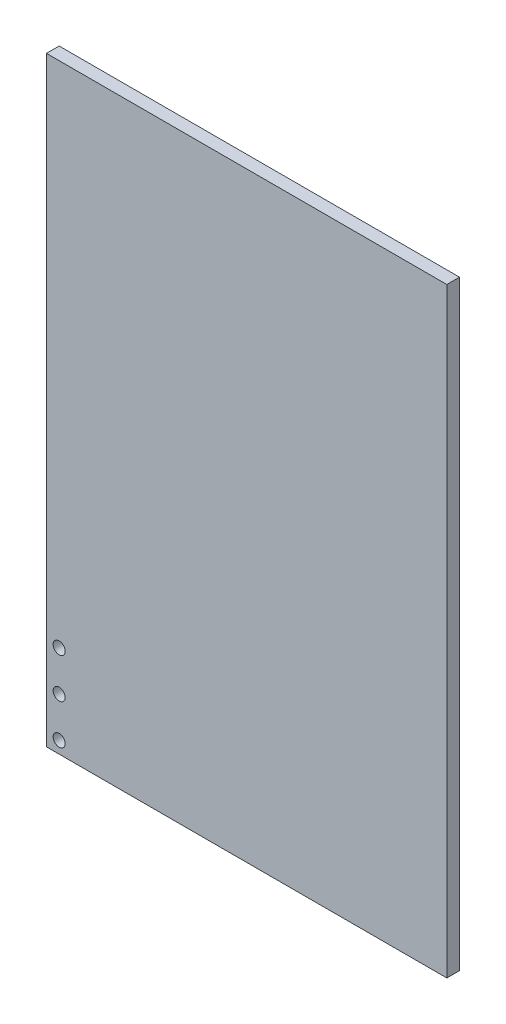
SolidWorks part; units mm, degrees
ref_plane "Front Plane" through (0, 0, 0) normal (0, 0, 1) x (1, 0, 0)
ref_plane "Top Plane" through (0, 0, 0) normal (0, 1, 0) x (1, 0, 0)
ref_plane "Right Plane" through (0, 0, 0) normal (1, 0, 0) x (0, 0, -1)
sketch "Sketch1" plane through (0, 0, 0) normal (0, 1, 0) x (1, 0, 0)
  line L1 (0, 0) -> (100, 0)
  line L2 (0, 0) -> (0, 3.175)
  line L3 (0, 3.175) -> (100, 3.175)
  line L4 (100, 0) -> (100, 3.175)
  dimension "D1" = 100
  dimension "D2" = 3.175
extrude "Boss-Extrude1" add sketch "Sketch1" along normal blind 150
sketch "Sketch2" plane through (0, 0, 0) normal (0, 0, 1) x (1, 0, 0)
  line L5 (0, 0) -> (6.35, 0)
  line L6 (0, 0) -> (0, 16)
  line L7 (0, 16) -> (6.35, 16)
  line L8 (6.35, 0) -> (6.35, 16)
  circle A3 centre (3.175, 13) radius 1.5
  circle A4 centre (3.175, 3) radius 1.5
  dimension "D5" = 3
  dimension "D6" = 3
  dimension "D7" = 3.175
  dimension "D3" = 3
  dimension "D4" = 3
  dimension "D1" = 6.35
  dimension "D2" = 16
  dimension "D8" = 3.175
extrude "Cut-Extrude2" cut sketch "Sketch2" against normal blind 3.175 contours A4 | A3
sketch "Sketch3" plane through (0, 0, 0) normal (0, 0, 1) x (1, 0, 0)
  line L0 (0, 150) -> (0, 0) construction
  circle A0 centre (3.175, 23) radius 1.5
  circle A1 centre (3.175, 13) radius 1.5 construction
  dimension "D1" = 3
  dimension "D2" = 10
  dimension "D3" = 3.175
extrude "Cut-Extrude3" cut sketch "Sketch3" against normal blind 3.175
